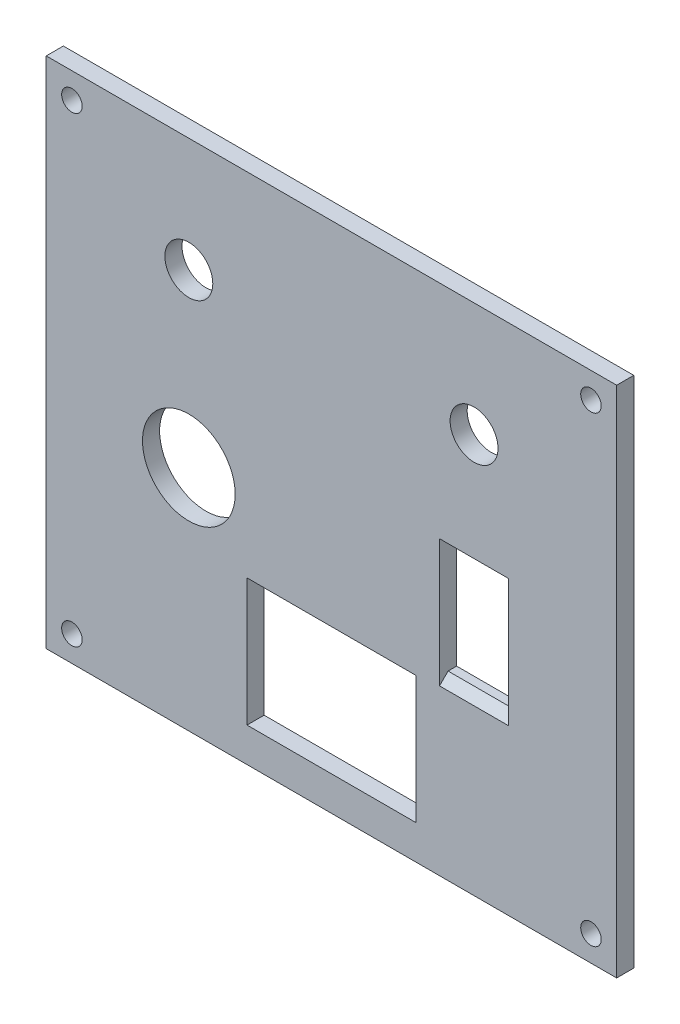
SolidWorks part; units mm, degrees
ref_plane "Front Plane" through (0, 0, 0) normal (0, 0, 1) x (1, 0, 0)
ref_plane "Top Plane" through (0, 0, 0) normal (0, 1, 0) x (1, 0, 0)
ref_plane "Right Plane" through (0, 0, 0) normal (1, 0, 0) x (0, 0, -1)
sketch "Sketch1" plane through (0, 0, 0) normal (0, 0, 1) x (1, 0, 0)
  line L0 (-25, 25) -> (25, 25) construction
  line L5 (-50, -45) -> (50, -45)
  line L6 (-50, -45) -> (-50, 45)
  line L7 (-50, 45) -> (50, 45)
  line L8 (50, -45) -> (50, 45)
  line L9 (0, 45) -> (0, -45) construction
  line L10 (-50, 0) -> (50, 0) construction
  line L11 (-14.8, -39) -> (14.8, -39)
  line L12 (-14.8, -39) -> (-14.8, -16.65)
  line L13 (-14.8, -16.65) -> (14.8, -16.65)
  line L14 (14.8, -39) -> (14.8, -16.65)
  line L15 (0, -16.65) -> (0, -39) construction
  line L16 (-14.8, -27.825) -> (14.8, -27.825) construction
  line L17 (25, 25) -> (25, -5) construction
  line L18 (-25, 25) -> (-25, -5) construction
  line L19 (25, -5) -> (-25, -5) construction
  line L20 (18.95, -14.675) -> (31.05, -14.675)
  line L21 (18.95, -14.675) -> (18.95, 4.675)
  line L22 (18.95, 4.675) -> (31.05, 4.675)
  line L23 (31.05, -14.675) -> (31.05, 4.675)
  line L24 (25, 4.675) -> (25, -14.675) construction
  line L25 (18.95, -5) -> (31.05, -5) construction
  circle A0 centre (0, 25) radius 4.2 construction
  circle A1 centre (25, 25) radius 4.2
  circle A2 centre (-25, 25) radius 4.2
  circle A3 centre (-25, -5) radius 8.125
  point P0 (0, 0)
  point P6 (0, -27.825)
  point P12 (0, 25)
  dimension "D6" = 8.4
  dimension "D12" = 16.25
  dimension "D1" = 100
  dimension "D2" = 90
  dimension "D3" = 22.35
  dimension "D4" = 29.6
  dimension "D5" = 6
  dimension "D11" = 20
  dimension "D13" = 30
  dimension "D14" = 12.1
  dimension "D15" = 19.35
  dimension "D9" = 50
  dimension "D7" = 2
  dimension "D8" = 2
extrude "Boss-Extrude1" add sketch "Sketch1" along normal blind 3
sketch "Sketch2" plane through (0, 0, 3) normal (0, 0, 1) x (1, 0, 0)
  line L0 (-50, 0) -> (50, 0) construction
  line L1 (-50, 45) -> (-41, 45)
  line L2 (-50, 45) -> (-50, 36)
  line L3 (-50, 36) -> (-41, 36)
  line L4 (-41, 45) -> (-41, 36)
  line L5 (-50, 45) -> (-50, -45) construction
  line L6 (50, -45) -> (50, 45) construction
  line L7 (0, 0) -> (0, -45) construction
  line L8 (-50, -45) -> (50, -45) construction
  line L9 (-50, -36) -> (-41, -36)
  line L10 (-41, -45) -> (-41, -36)
  line L11 (-50, -45) -> (-41, -45)
  line L12 (-50, -45) -> (-50, -36)
  line L13 (50, -45) -> (50, -36)
  line L14 (50, -45) -> (41, -45)
  line L15 (41, -45) -> (41, -36)
  line L16 (50, -36) -> (41, -36)
  line L17 (50, 36) -> (41, 36)
  line L18 (41, 45) -> (41, 36)
  line L19 (50, 45) -> (41, 45)
  line L20 (50, 45) -> (50, 36)
  line L21 (-50, 4) -> (-42, 4)
  line L22 (-42, 4) -> (-42, -4)
  line L23 (-50, -4) -> (-42, -4)
  line L24 (-50, -4) -> (-50, 4)
  line L25 (50, -4) -> (42, -4)
  line L26 (42, 4) -> (42, -4)
  line L27 (50, 4) -> (42, 4)
  line L28 (50, -4) -> (50, 4)
  line L29 (-45.5, 36) -> (-45.5, 45) construction
  line L30 (-41, 40.5) -> (-45.5, 40.5) construction
  point P31 (-42, 0)
  dimension "D1" = 9
  dimension "D2" = 8
  dimension "D3" = 8
hole_wizard "M3 Clearance Hole1" positions "Sketch3" profile "Sketch4" hole size "M3" standard "DIN" end condition up to next
sketch "Sketch3" plane through (0, 0, 3) normal (0, 0, 1) x (1, 0, 0)
  point P0 (-45.5, 40.5)
sketch "Sketch4" plane through (-45.5, 40.5, 3) normal (1, 0, 0) x (0, -1, 0)
  line L0 (0, 0) -> (0, 3)
  line L1 (0, 3) -> (1.8, 3)
  line L2 (1.8, 3) -> (1.8, 0)
  line L5 (1.8, 0) -> (0, 0)
  line L11 (0, -6.35) -> (0, 107.95) construction
  dimension "Thru Hole Dia." = 3.6
  dimension "Thru Hole Depth" = 3
mirror "Mirror1" about plane through (0, 0, 0) normal (0, 1, 0) of "M3 Clearance Hole1"
mirror "Mirror2" about plane through (0, 0, 0) normal (1, 0, 0) of "Mirror1", "M3 Clearance Hole1"
chamfer "Chamfer1" distance 1.5 angle 45 2 edges at (25, -14.675, 3) (25, 4.675, 3)
equation "\"Hole Tollerance\"= 0.6mm"
equation "\"D4@Sketch1\"=\"Hole Tollerance\"+29"
equation "\"D3@Sketch1\"=\"Hole Tollerance\"+21.75"
equation "\"D12@Sketch1\"=\"Hole Tollerance\" + 15.65"
equation "\"D14@Sketch1\"=\"Hole Tollerance\" + 11.5"
equation "\"D15@Sketch1\"=\"Hole Tollerance\" + 18.75"
